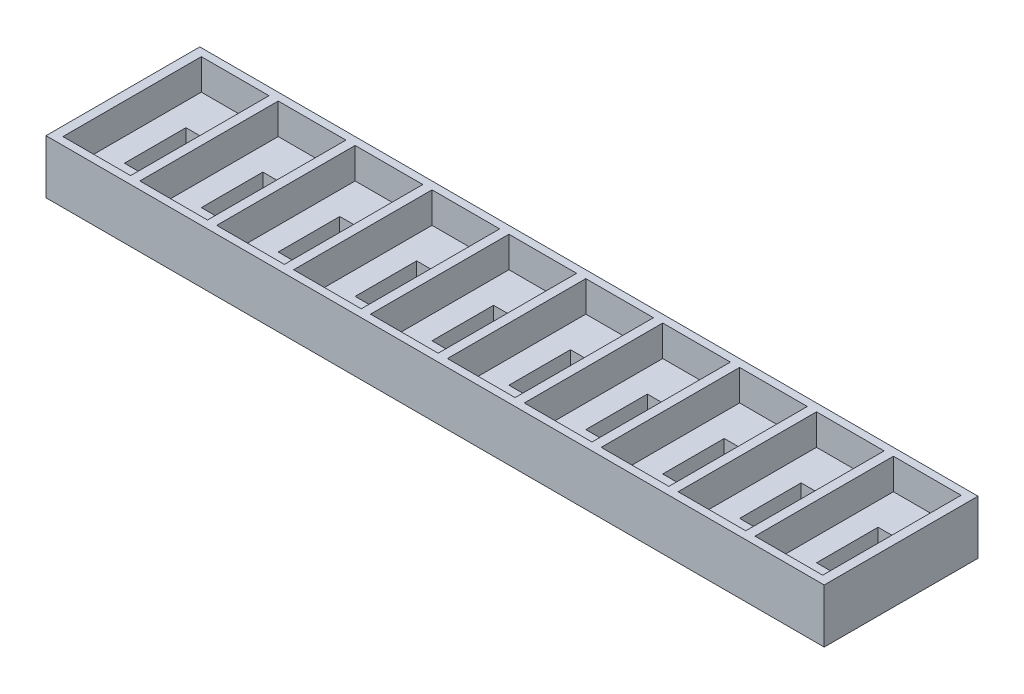
SolidWorks part; units mm, degrees
ref_plane "Front Plane" through (0, 0, 0) normal (0, 0, 1) x (1, 0, 0)
ref_plane "Top Plane" through (0, 0, 0) normal (0, 1, 0) x (1, 0, 0)
ref_plane "Right Plane" through (0, 0, 0) normal (1, 0, 0) x (0, 0, -1)
sketch "Sketch1" plane through (0, 0, 0) normal (0, 1, 0) x (1, 0, 0)
  line L1 (0, 0) -> (253, 0)
  line L2 (0, 0) -> (0, -50)
  line L3 (0, -50) -> (253, -50)
  line L4 (253, 0) -> (253, -50)
  point P5 (0, 0)
  point P6 (0, 0)
  point P7 (0, 0)
  point P8 (0, 0)
extrude "Boss-Extrude1" add sketch "Sketch1" along normal blind 17.5
sketch "Sketch2" plane through (0, 17.5, 0) normal (0, 1, 0) x (1, 0, 0)
  line L1 (3, -2.5) -> (25, -2.5)
  line L2 (3, -2.5) -> (3, -47.5)
  line L3 (3, -47.5) -> (25, -47.5)
  line L4 (25, -2.5) -> (25, -47.5)
  point P4 (0, 0)
  point P5 (9.613, -5.6042)
  point P6 (9.613, -45.6782)
  point P7 (45.5193, -7.8483)
  point P8 (45.5193, -45.6782)
  point P9 (0, 0)
  point P10 (45.5193, -5.6042)
  point P11 (0, 0)
  point P12 (0, 0)
  point P13 (0, 0)
  point P14 (0, 0)
  point P15 (0, 0)
  point P16 (0, 0)
  point P17 (0, 0)
  point P18 (0, 0)
  point P19 (0, 0)
  point P20 (0, 0)
  point P21 (0, 0)
  point P22 (0, 0)
  point P23 (0, 0)
  point P24 (0, 0)
  point P25 (0, 0)
  point P26 (0, 0)
  point P27 (0, 0)
  point P28 (0, 0)
  point P29 (0, 0)
  point P30 (0, 0)
  point P31 (0, 0)
  point P32 (0, 0)
  point P33 (0, 0)
  point P34 (0, 0)
  point P35 (0, 0)
  point P36 (0, 0)
  point P37 (0, 0)
extrude "Cut-Extrude1" cut sketch "Sketch2" against normal blind 10
sketch "Sketch3" plane through (0, 17.5, 0) normal (0, 1, 0) x (1, 0, 0)
  line L1 (10.5, -15) -> (25, -15)
  line L2 (10.5, -15) -> (10.5, -35)
  line L3 (10.5, -35) -> (25, -35)
  line L4 (25, -15) -> (25, -35)
  point P4 (0, 0)
  point P5 (0, 0)
  point P6 (0, 0)
  point P7 (0, 0)
  point P8 (0, 0)
  point P9 (0, 0)
  point P10 (0, 0)
  point P11 (0, 0)
  point P12 (0, 0)
  point P13 (0, 0)
  point P14 (0, 0)
  point P15 (0, 0)
  point P16 (0, 0)
  point P17 (0, 0)
  point P18 (0, 0)
  point P19 (0, 0)
  point P20 (0, 0)
  point P21 (0, 0)
  point P23 (0, 0)
  point P24 (0, 0)
  point P25 (0, 0)
  point P26 (0, 0)
  point P27 (0, 0)
extrude "Cut-Extrude2" cut sketch "Sketch3" against normal blind 17.5
pattern_linear "LPattern1" count 10 spacing 25 along (1, 0, 0) of "Cut-Extrude1", "Cut-Extrude2"
